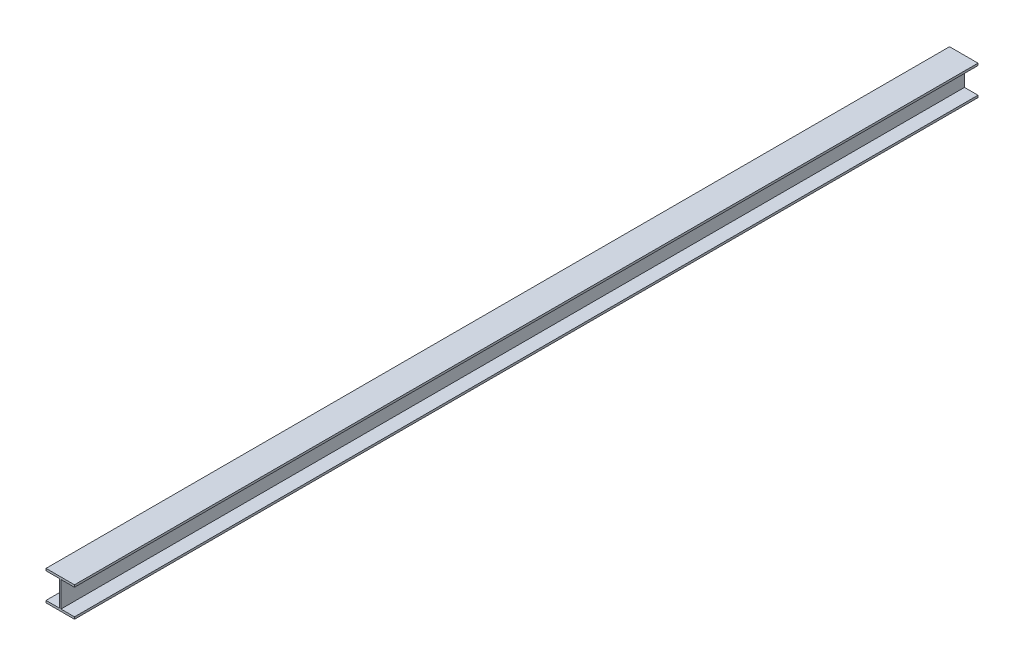
SolidWorks part; units mm, degrees
material "ASTM A992 Steel"
ref_plane "Front" through (0, 0, 0) normal (0, 0, 1) x (1, 0, 0)
ref_plane "Top" through (0, 0, 0) normal (0, 1, 0) x (1, 0, 0)
ref_plane "Right" through (0, 0, 0) normal (1, 0, 0) x (0, 0, -1)
sketch "Sketch1" plane through (0, 0, 0) normal (0, 0, 1) x (1, 0, 0)
  line L0 (0, -0.0002) -> (154.432, -0.0002)
  line L1 (154.432, -0.0002) -> (154.432, -11.5572)
  line L2 (154.432, -11.5572) -> (81.28, -11.5572)
  line L3 (81.28, -11.5572) -> (81.28, -150.4952)
  line L4 (81.28, -150.4952) -> (154.432, -150.4952)
  line L5 (154.432, -150.4952) -> (154.432, -162.0522)
  line L6 (154.432, -162.0522) -> (0, -162.0522)
  line L7 (0, -162.0522) -> (0, -150.4952)
  line L8 (0, -150.4952) -> (73.152, -150.4952)
  line L9 (73.152, -150.4952) -> (73.152, -11.5572)
  line L10 (73.152, -11.5572) -> (0, -11.5572)
  line L11 (0, -11.5572) -> (0, -0.0002)
  line L12 (77.216, -0.0002) -> (77.216, -162.0522) construction
  point P15 (154.432, -156.2737)
  dimension "D1" = 8.128
  dimension "D2" = 11.557
  dimension "D3" = 11.557
  dimension "D4" = 11.557
  dimension "D5" = 162.052
  dimension "D6" = 4.064
  dimension "D7" = 77.216
  dimension "D8" = 77.216
extrude "Boss-Extrude1" add sketch "Sketch1" along normal blind 4900
